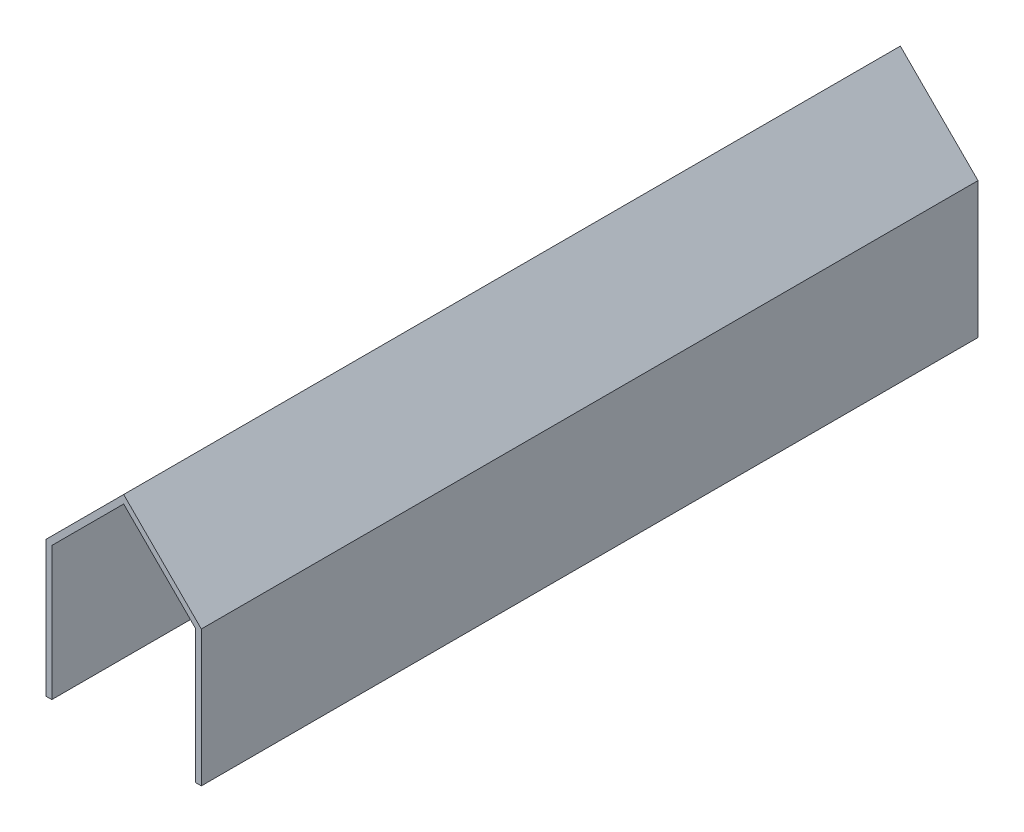
SolidWorks part; units mm, degrees
ref_plane "Front Plane" through (0, 0, 0) normal (0, 0, 1) x (1, 0, 0)
ref_plane "Top Plane" through (0, 0, 0) normal (0, 1, 0) x (1, 0, 0)
ref_plane "Right Plane" through (0, 0, 0) normal (1, 0, 0) x (0, 0, -1)
sketch "Sketch1" plane through (0, 0, 0) normal (0, 0, 1) x (1, 0, 0)
  line L0 (0, 105.7574) -> (0, 0) construction
  line L1 (-37, 0) -> (-37, 68.7574)
  line L2 (-37, 68.7574) -> (0, 105.7574)
  line L4 (0, 110) -> (-40, 70)
  line L5 (-40, 70) -> (-40, 0)
  line L6 (-40, 0) -> (-37, 0)
  line L7 (37, 68.7574) -> (0, 105.7574)
  line L8 (0, 110) -> (40, 70)
  line L9 (40, 70) -> (40, 0)
  line L10 (40, 0) -> (37, 0)
  line L11 (37, 0) -> (37, 68.7574)
  point P0 (0, -8.1207)
  point P5 (0, 0)
  dimension "D1" = 3
  dimension "D2" = 80
  dimension "D3" = 70
  dimension "D4" = 3
  dimension "D5" = 40
extrude "Boss-Extrude1" add sketch "Sketch1" along normal blind 400
